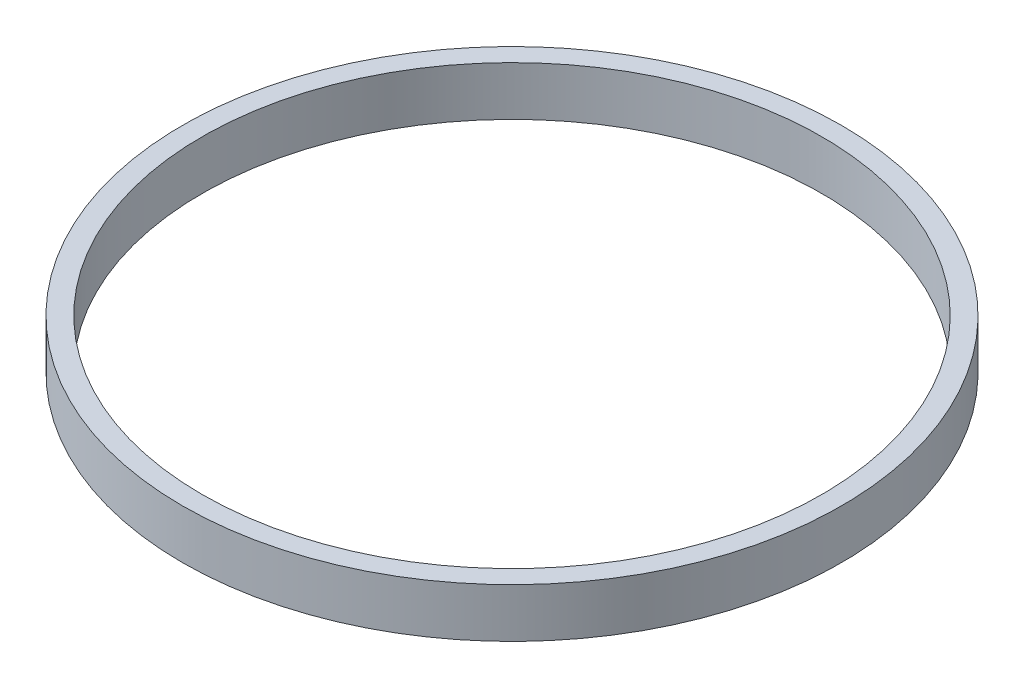
SolidWorks part; units mm, degrees
ref_plane "Front Plane" through (0, 0, 0) normal (0, 0, 1) x (1, 0, 0)
ref_plane "Top Plane" through (0, 0, 0) normal (0, 1, 0) x (1, 0, 0)
ref_plane "Right Plane" through (0, 0, 0) normal (1, 0, 0) x (0, 0, -1)
sketch "Sketch1" plane through (0, 0, 0) normal (0, 1, 0) x (1, 0, 0)
  circle A0 centre (0, 0) radius 31.5
  circle A1 centre (0, 0) radius 33.5
  dimension "D1" = 63
  dimension "D2" = 2
extrude "Boss-Extrude1" add sketch "Sketch1" along normal blind 5
